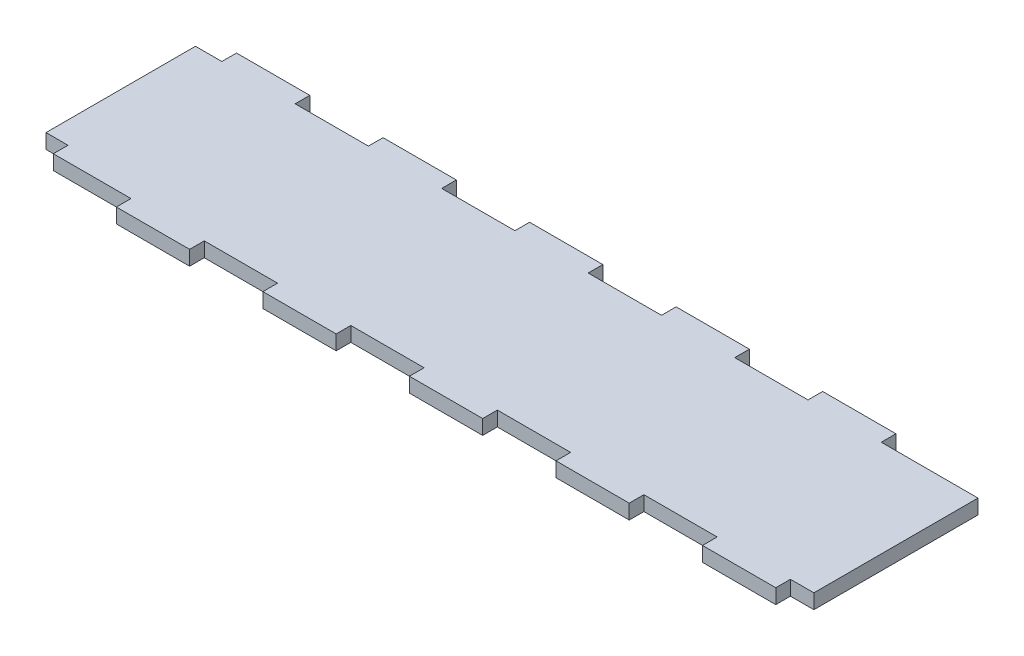
SolidWorks part; units mm, degrees
ref_plane "Front Plane" through (0, 0, 0) normal (0, 0, 1) x (1, 0, 0)
ref_plane "Top Plane" through (0, 0, 0) normal (0, 1, 0) x (1, 0, 0)
ref_plane "Right Plane" through (0, 0, 0) normal (1, 0, 0) x (0, 0, -1)
sketch "Sketch1" plane through (0, 0, 0) normal (0, 1, 0) x (1, 0, 0)
  line L0 (25, 56) -> (50, 56)
  line L2 (258, 0) -> (250, 0)
  line L3 (-1.5, 0) -> (-1.5, 5)
  line L4 (0, 61) -> (25, 61)
  line L5 (0, 56) -> (0, 61)
  line L6 (25, 56) -> (25, 61)
  line L7 (50, 56) -> (50, 61)
  line L8 (75, 56) -> (75, 61)
  line L9 (100, 56) -> (100, 61)
  line L10 (125, 56) -> (125, 61)
  line L11 (150, 56) -> (150, 61)
  line L12 (175, 56) -> (175, 61)
  line L13 (200, 56) -> (200, 61)
  line L14 (225, 56) -> (225, 61)
  line L15 (-1.5, 5) -> (-9, 5)
  line L16 (258, 56) -> (258, -0.0069)
  line L18 (225, 0) -> (225, -5)
  line L19 (200, 0) -> (200, -5)
  line L20 (175, 0) -> (175, -5)
  line L21 (150, 0) -> (150, -5)
  line L22 (125, 0) -> (125, -5)
  line L23 (100, 0) -> (100, -5)
  line L24 (75, 0) -> (75, -5)
  line L25 (50, 0) -> (50, -5)
  line L26 (25, 0) -> (25, -5)
  line L27 (250, 0) -> (250, -5)
  line L28 (0, 56) -> (-9, 56)
  line L29 (-9, 56) -> (-9, 5)
  line L31 (50, 61) -> (75, 61)
  line L32 (100, 61) -> (125, 61)
  line L33 (150, 61) -> (175, 61)
  line L34 (200, 61) -> (225, 61)
  line L35 (250, -5) -> (225, -5)
  line L36 (200, -5) -> (175, -5)
  line L37 (150, -5) -> (125, -5)
  line L38 (100, -5) -> (75, -5)
  line L39 (50, -5) -> (25, -5)
  line L40 (75, 56) -> (100, 56)
  line L41 (125, 56) -> (150, 56)
  line L42 (175, 56) -> (200, 56)
  line L43 (225, 56) -> (258, 56)
  line L44 (225, 0) -> (200, 0)
  line L45 (175, 0) -> (150, 0)
  line L46 (125, 0) -> (100, 0)
  line L47 (75, 0) -> (50, 0)
  line L48 (25, 0) -> (-1.5, 0)
  dimension "D2" = 5
  dimension "D13" = 5
  dimension "D14" = 267
  dimension "D12" = 7.5
  dimension "D3" = 25
  dimension "D4" = 25
  dimension "D5" = 25
  dimension "D6" = 25
  dimension "D7" = 25
  dimension "D8" = 25
  dimension "D9" = 25
  dimension "D10" = 25
  dimension "D11" = 25
extrude "Boss-Extrude1" add sketch "Sketch1" along normal blind 5 contours L48 L26 L39 L25 L47 L24 L38 L23 L46 L22 L37 L21 L45 L20 L36 L19 L44 L18 L35 L27 L2 L16 L43 L14 L34 L13 L42 L12 L33 L11 L41 L10 L32 L9 L40 L8 L31 L7 L0 L6 L4 L5 L28 L29 L15 L3
